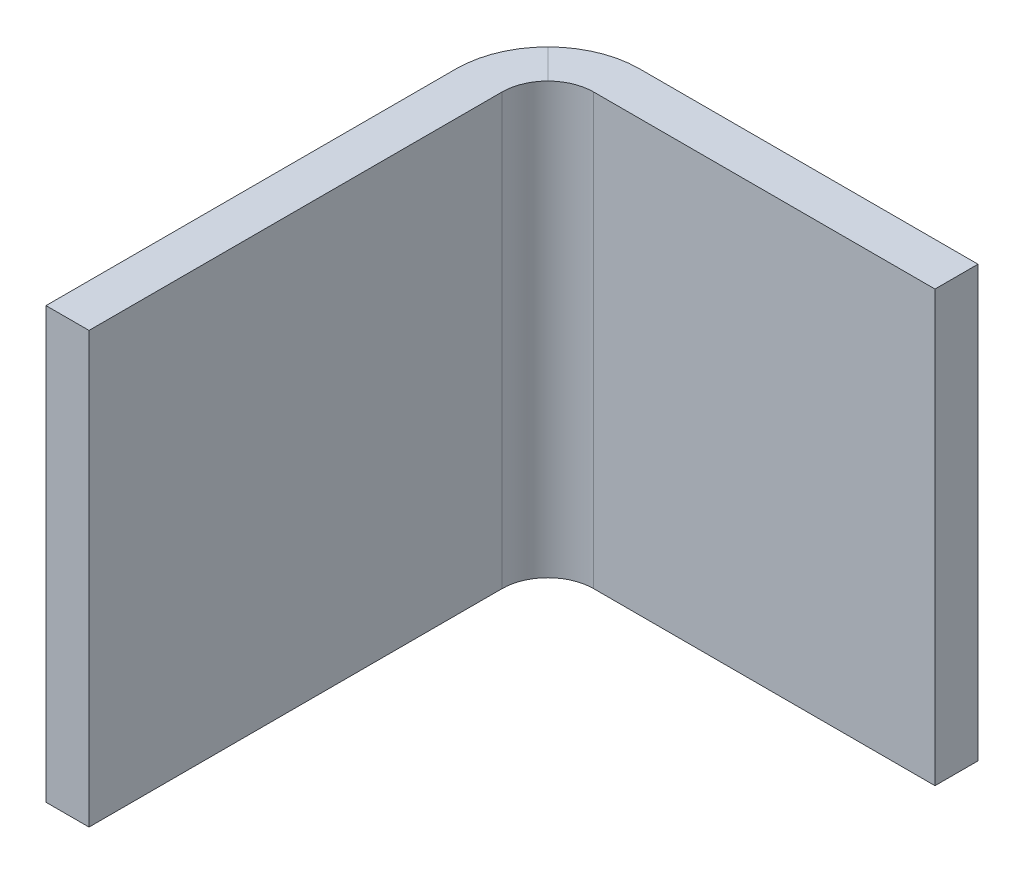
SolidWorks part; units mm, degrees
ref_plane "Front Plane" through (0, 0, 0) normal (0, 0, 1) x (1, 0, 0)
ref_plane "Top Plane" through (0, 0, 0) normal (0, 1, 0) x (1, 0, 0)
ref_plane "Right Plane" through (0, 0, 0) normal (1, 0, 0) x (0, 0, -1)
sketch "Sketch1" plane through (0, 0, 0) normal (0, 0, 1) x (1, 0, 0)
  line L0 (0, 15) -> (0, -15)
  line L1 (0, 0) -> (3, 0)
  point P4 (0, 0)
  point P8 (0, 0)
  point P9 (0, 0)
sketch "Sketch2" plane through (0, 0, 0) normal (0, 1, 0) x (1, 0, 0)
  line L0 (0, 0) -> (0, 31.8)
  line L1 (3.2, 35) -> (30, 35)
  arc A0 (3.2, 35) -> (0, 31.8) centre (3.2, 31.8) ccw
  point P6 (0, 35)
sketch "Sketch3" plane through (0, 0, 0) normal (0, 0, 1) x (1, 0, 0)
  line L8 (3, -15) -> (0, -15)
  line L9 (3, -15) -> (3, 15)
  line L10 (0, -15) -> (0, 15)
  line L11 (3, 15) -> (0, 15)
  line L12 (3, -15) -> (0, 15) construction
  line L13 (0, -15) -> (3, 15) construction
  line L14 (0, 0) -> (3, 0) construction
  point P1 (0, 0)
  point P2 (1.5, 0)
  dimension "D1" = 3
  dimension "D2" = 30
  dimension "D3" = 15
sketch "Sketch4" plane through (0, 0, 0) normal (0, 1, 0) x (1, 0, 0)
  line L0 (0, 0) -> (0, 35)
  line L1 (0, 35) -> (30, 35)
  dimension "D2" = 30
  dimension "D1" = 35
sweep "Sweep1" add profiles "Sketch3" path "Sketch4"
fillet "Fillet1" radius 3.2 1 edges at (3, 0, -32)
fillet "Fillet2" radius 6.4 1 edges at (0, 0, -35)
equation "\"D1@Sketch3\"=\"Thickness@Sketch1\""
equation "\"D2@Sketch3\"=\"LengthC@Sketch1\""
equation "\"D3@Sketch3\"=\"LengthC@Sketch1\"/2"
equation "\"D1@Sketch4\"=\"LengthA@Sketch2\""
equation "\"D2@Sketch4\"=\"LengthB@Sketch2\""
equation "\"D1@Fillet1\"=\"CornerRadius@Sketch2\""
equation "\"D1@Fillet2\"=\"CornerRadius@Sketch2\"*2"
